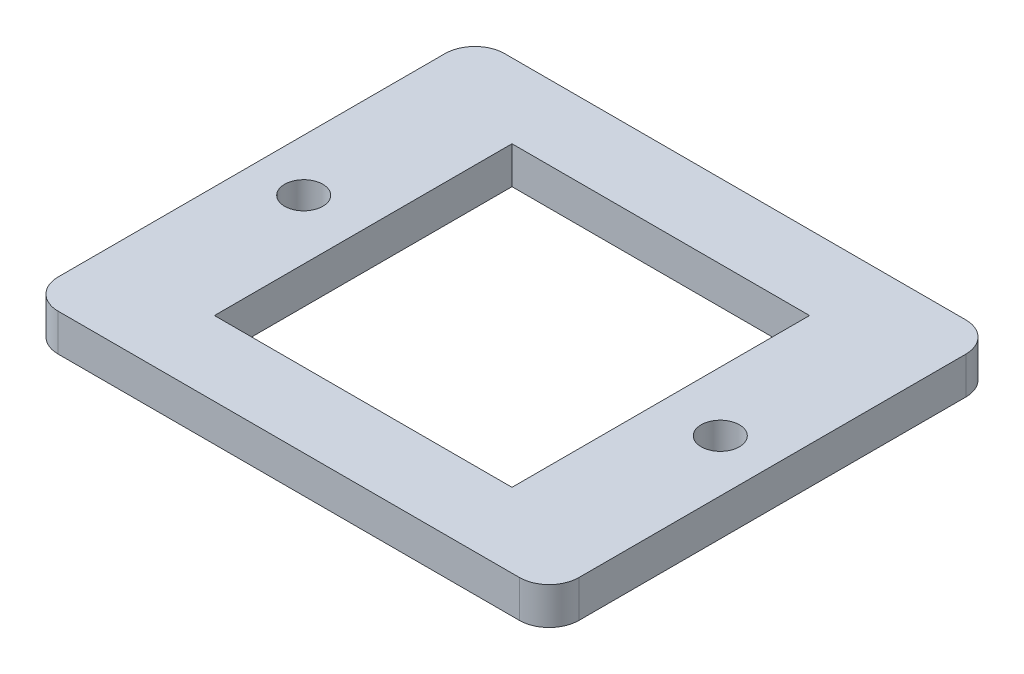
SolidWorks part; units mm, degrees
ref_plane "Front Plane" through (0, 0, 0) normal (0, 0, 1) x (1, 0, 0)
ref_plane "Top Plane" through (0, 0, 0) normal (0, 1, 0) x (1, 0, 0)
ref_plane "Right Plane" through (0, 0, 0) normal (1, 0, 0) x (0, 0, -1)
sketch "Sketch1" plane through (0, 0, 0) normal (0, 1, 0) x (1, 0, 0)
  line L1 (-22.225, 19.05) -> (22.225, 19.05)
  line L2 (-22.225, 19.05) -> (-22.225, -19.05)
  line L3 (-22.225, -19.05) -> (22.225, -19.05)
  line L4 (22.225, 19.05) -> (22.225, -19.05)
  line L5 (-22.225, 19.05) -> (22.225, -19.05) construction
  line L6 (-22.225, -19.05) -> (22.225, 19.05) construction
  point P0 (0, 0)
  dimension "D1" = 44.45
  dimension "D2" = 38.1
extrude "Boss-Extrude1" add sketch "Sketch1" along normal blind 3.175
sketch "Sketch2" plane through (0, 3.175, 0) normal (0, 1, 0) x (1, 0, 0)
  line L1 (-12.7, 12.7) -> (12.7, 12.7)
  line L2 (-12.7, 12.7) -> (-12.7, -12.7)
  line L3 (-12.7, -12.7) -> (12.7, -12.7)
  line L4 (12.7, 12.7) -> (12.7, -12.7)
  line L5 (-12.7, 12.7) -> (12.7, -12.7) construction
  line L6 (-12.7, -12.7) -> (12.7, 12.7) construction
  point P0 (0, 0)
  dimension "D1" = 25.4
  dimension "D2" = 25.4
extrude "Cut-Extrude1" cut sketch "Sketch2" against normal blind 3.175
hole_wizard "#4 Clearance Hole1" positions "Sketch4" profile "Sketch3" hole size "#4" standard "ANSI Inch"
sketch "Sketch4" plane through (0, 3.175, 0) normal (0, 1, 0) x (1, 0, 0)
  line L0 (-12.7, 12.7) -> (-12.7, -12.7) construction
  line L1 (12.7, -12.7) -> (12.7, 12.7) construction
  line L2 (12.7, 12.7) -> (-12.7, 12.7) construction
  point P0 (-17.78, 0)
  point P2 (17.78, 0)
  point P9 (12.7, 0)
  dimension "D1" = 5.08
  dimension "D2" = 5.08
  dimension "D3" = 12.7
  dimension "D4" = 12.7
sketch "Sketch3" plane through (-17.78, 3.175, 0) normal (1, 0, 0) x (0, 0, 1)
  line L0 (0, 0) -> (0, 11.1406)
  line L1 (0, 11.1406) -> (1.6319, 10.16)
  line L2 (1.6319, 10.16) -> (1.6319, 0)
  line L5 (1.6319, 0) -> (0, 0)
  line L10 (0, 11.1406) -> (-1.6319, 10.16) construction
  line L11 (0, -6.35) -> (0, 107.95) construction
  dimension "Hole Dia." = 3.2639
  dimension "Hole Depth" = 10.16
  dimension "Drill Angle" = 118
fillet "Fillet1" radius 2.54 4 edges at (22.225, 1.5875, 19.05) (22.225, 1.5875, -19.05) (-22.225, 1.5875, -19.05) (-22.225, 1.5875, 19.05)
